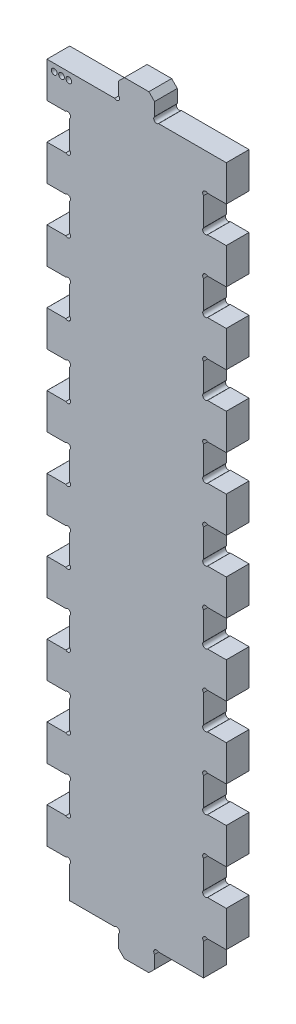
SolidWorks part; units mm, degrees
material "PVC Rigid"
ref_plane "Front Plane" through (0, 0, 0) normal (0, 0, 1) x (1, 0, 0)
ref_plane "Top Plane" through (0, 0, 0) normal (0, 1, 0) x (1, 0, 0)
ref_plane "Right Plane" through (0, 0, 0) normal (1, 0, 0) x (0, 0, -1)
sketch "Model" [suppressed]
  dimension "D3" = 0.7937
  dimension "D1" = 10
  dimension "D2" = 10
sketch "Sketch1" plane through (0, 0, 0) normal (0, 0, 1) x (1, 0, 0)
  line L1 (0, 0) -> (50, 0)
  line L2 (0, 0) -> (0, 200.0001)
  line L3 (0, 200.0001) -> (50, 200.0001)
  line L4 (50, 0) -> (50, 200.0001)
  dimension "D1" = 200.0001
  dimension "D2" = 50
extrude "Boss-Extrude1" add sketch "Sketch1" along normal blind 6.35
sketch "Sketch2" plane through (0, 0, 0) normal (0, 0, 1) x (1, 0, 0)
  line L0 (0, 100.0001) -> (50, 100.0001) construction
  line L1 (50, 200.0001) -> (0, 200.0001) construction
  line L2 (25, 200.0001) -> (25, 203.1751) construction
  line L3 (20, 206.3501) -> (30, 206.3501)
  line L4 (20, 206.3501) -> (20, 200.0001)
  line L5 (20, 200.0001) -> (30, 200.0001)
  line L6 (30, 206.3501) -> (30, 200.0001)
  line L7 (20, 206.3501) -> (30, 200.0001) construction
  line L8 (20, 200.0001) -> (30, 206.3501) construction
  line L9 (0, 200.0001) -> (0, 0) construction
  line L10 (50, 0) -> (50, 200.0001) construction
  line L11 (20, 0) -> (30, -6.35) construction
  line L12 (20, -6.35) -> (30, 0) construction
  line L13 (25, 0) -> (25, -3.175) construction
  line L14 (30, -6.35) -> (30, 0)
  line L15 (20, 0) -> (30, 0)
  line L16 (20, -6.35) -> (20, 0)
  line L17 (20, -6.35) -> (30, -6.35)
  dimension "D1" = 6.35
  dimension "D2" = 10
extrude "Boss-Extrude2" add sketch "Sketch2" along normal blind 6.35
sketch "Sketch3" plane through (0, 0, 6.35) normal (0, 0, 1) x (1, 0, 0)
  line L0 (25, 206.3501) -> (25, -6.35) construction
  line L1 (30, 206.3501) -> (20, 206.3501) construction
  line L2 (20, -6.35) -> (30, -6.35) construction
  line L3 (6.35, 200.0001) -> (6.35, 0) construction
  line L4 (20, 200.0001) -> (0, 200.0001) construction
  line L5 (0, 0) -> (20, 0) construction
  line L6 (0, 200.0001) -> (0, 0) construction
  line L7 (6.35, 0) -> (0, 0)
  line L8 (6.35, 0) -> (6.35, 10)
  line L9 (6.35, 10) -> (0, 10)
  line L10 (0, 0) -> (0, 10)
  line L11 (50, 0) -> (50, 10)
  line L12 (43.65, 10) -> (50, 10)
  line L13 (43.65, 0) -> (43.65, 10)
  line L14 (43.65, 0) -> (50, 0)
  dimension "D1" = 6.35
  dimension "D2" = 10
extrude "Cut-Extrude1" cut sketch "Sketch3" against normal blind 6.35
pattern_linear "LPattern2" count 10 spacing 20 along (0, 1, 0) of "Cut-Extrude1"
sketch "Sketch4" plane through (0, 0, 6.35) normal (0, 0, 1) x (1, 0, 0)
  line L0 (0, 10) -> (6.35, 0) construction
  line L1 (6.35, 10) -> (5.2275, 10) construction
  line L2 (0.5613, 0.5613) -> (5.7887, 0.5613) construction
  line L3 (0.5613, 0.5613) -> (0.5613, 9.4387) construction
  line L4 (0.5613, 9.4387) -> (5.7887, 9.4387) construction
  line L5 (5.7887, 0.5613) -> (5.7887, 9.4387) construction
  line L6 (0.5613, 0.5613) -> (5.7887, 9.4387) construction
  line L7 (0.5613, 9.4387) -> (5.7887, 0.5613) construction
  line L8 (6.35, 10) -> (0, 10) construction
  line L9 (6.35, 10) -> (6.35, 8.8775) construction
  line L10 (6.35, 0) -> (6.35, 10) construction
  line L11 (25, 206.3501) -> (25, -6.35) construction
  line L12 (30, 206.3501) -> (20, 206.3501) construction
  line L13 (20, -6.35) -> (30, -6.35) construction
  line L14 (44.2113, 9.4387) -> (44.2113, 20.5613) construction
  line L15 (43.65, 10) -> (43.65, 8.8775) construction
  line L16 (49.4387, 9.4387) -> (44.2113, 0.5613) construction
  line L17 (49.4387, 0.5613) -> (44.2113, 9.4387) construction
  line L18 (44.2113, 0.5613) -> (44.2113, 9.4387) construction
  line L19 (49.4387, 9.4387) -> (44.2113, 9.4387) construction
  line L20 (49.4387, 0.5613) -> (49.4387, 9.4387) construction
  line L21 (49.4387, 0.5613) -> (44.2113, 0.5613) construction
  line L22 (43.65, 10) -> (44.7725, 10) construction
  line L23 (5.7887, 9.4387) -> (5.7887, 20.5613) construction
  line L24 (50, 10) -> (43.65, 0) construction
  circle A0 centre (5.7887, 9.4387) radius 0.7938
  circle A4 centre (5.7887, 20.5613) radius 0.7938
  circle A7 centre (44.2113, 20.5613) radius 0.7937
  circle A8 centre (44.2113, 9.4387) radius 0.7937
  point P4 (3.175, 5)
  point P40 (46.825, 5)
  dimension "D1" = 1.5875
extrude "Cut-Extrude3" cut sketch "Sketch4" against normal blind 6.35
pattern_linear "LPattern3" count 9 spacing 20 along (0, 1, 0) of "Cut-Extrude3"
sketch "Sketch8" [suppressed] plane through (0, 0, 6.35) normal (0, 0, 1) x (1, 0, 0)
  line L0 (6.35, 200.0001) -> (6.35, 0) construction
  line L1 (20, 200.0001) -> (0, 200.0001) construction
  line L2 (0, 0) -> (20, 0) construction
  line L3 (0, 200.0001) -> (0, 0) construction
  line L4 (43.65, 200.0001) -> (43.65, 0) construction
  line L5 (0, 0) -> (6.35, 0)
  line L6 (0, 0) -> (0, 10)
  line L7 (0, 10) -> (6.35, 10)
  line L8 (6.35, 0) -> (6.35, 10)
  line L9 (50, 200.0001) -> (30, 200.0001) construction
  line L10 (30, 0) -> (50, 0) construction
  line L11 (50, 0) -> (50, 200.0001) construction
  line L12 (43.65, 10) -> (50, 10)
  line L13 (43.65, 10) -> (43.65, 20)
  line L14 (43.65, 20) -> (50, 20)
  line L15 (50, 10) -> (50, 20)
  dimension "D1" = 6.35
  dimension "D2" = 10
  dimension "D3" = 10
  dimension "D4" = 6.35
  dimension "D5" = 10
extrude "Cut-Extrude6" [suppressed] cut sketch "Sketch8" against normal through all
pattern_linear "LPattern4" [suppressed] count 10 spacing 20
sketch "Sketch9" [suppressed] plane through (0, 0, 6.35) normal (0, 0, 1) x (1, 0, 0)
  line L0 (0, 30) -> (6.35, 20) construction
  line L1 (6.35, 30) -> (5.2275, 30) construction
  line L2 (0.5613, 20.5613) -> (5.7887, 20.5613) construction
  line L3 (0.5613, 20.5613) -> (0.5613, 29.4388) construction
  line L4 (0.5613, 29.4388) -> (5.7887, 29.4388) construction
  line L5 (5.7887, 20.5613) -> (5.7887, 29.4388) construction
  line L6 (0.5613, 20.5613) -> (5.7887, 29.4388) construction
  line L7 (0.5613, 29.4388) -> (5.7887, 20.5613) construction
  line L8 (6.35, 30) -> (0, 30) construction
  line L9 (6.35, 30) -> (6.35, 28.8775) construction
  line L10 (6.35, 20) -> (6.35, 30) construction
  line L11 (43.65, 20) -> (50, 10) construction
  line L12 (43.65, 20) -> (44.7725, 20) construction
  line L13 (44.2113, 10.5613) -> (49.4387, 10.5613) construction
  line L14 (44.2113, 10.5613) -> (44.2113, 19.4387) construction
  line L15 (44.2113, 19.4387) -> (49.4387, 19.4387) construction
  line L16 (49.4387, 10.5613) -> (49.4387, 19.4387) construction
  line L17 (44.2113, 10.5613) -> (49.4387, 19.4387) construction
  line L18 (44.2113, 19.4387) -> (49.4387, 10.5613) construction
  line L19 (50, 20) -> (43.65, 20) construction
  line L20 (43.65, 20) -> (43.65, 18.8775) construction
  line L21 (43.65, 20) -> (43.65, 10) construction
  line L22 (50, 20) -> (50, 30) construction
  circle A0 centre (5.7887, 29.4388) radius 0.7938
  circle A1 centre (5.7887, 20.5613) radius 0.7938
  circle A2 centre (44.2113, 19.4387) radius 0.7937
  circle A3 centre (44.2113, 10.5613) radius 0.7937
  point P4 (3.175, 25)
  point P23 (46.825, 15)
  dimension "D1" = 1.5875
  dimension "D2" = 10
extrude "Cut-Extrude7" [suppressed] cut sketch "Sketch9" against normal through all
pattern_linear "LPattern5" [suppressed] count 9 spacing 20
sketch "Sketch10" [suppressed] plane through (0, 0, 6.35) normal (0, 0, 1) x (1, 0, 0)
  line L0 (0, 10) -> (6.35, 0) construction
  line L1 (5.2275, 10) -> (6.35, 10) construction
  line L2 (0.5613, 0.5613) -> (5.7887, 0.5613) construction
  line L3 (0.5613, 0.5613) -> (0.5613, 9.4387) construction
  line L4 (0.5613, 9.4387) -> (5.7887, 9.4387) construction
  line L5 (5.7887, 0.5613) -> (5.7887, 9.4387) construction
  line L6 (0.5613, 0.5613) -> (5.7887, 9.4387) construction
  line L7 (0.5613, 9.4387) -> (5.7887, 0.5613) construction
  line L8 (6.35, 10) -> (0, 10) construction
  line L9 (6.35, 10) -> (6.35, 8.8775) construction
  line L10 (6.35, 0) -> (6.35, 10) construction
  line L11 (6.35, 5) -> (3.175, 5) construction
  line L12 (0, 200.0001) -> (50, 0) construction
  line L13 (43.65, 200.0001) -> (50, 190.0001) construction
  line L14 (44.7725, 190.0001) -> (43.65, 190.0001) construction
  line L15 (44.2113, 190.5614) -> (49.4387, 190.5614) construction
  line L16 (44.2113, 190.5614) -> (44.2113, 199.4388) construction
  line L17 (44.2113, 199.4388) -> (49.4387, 199.4388) construction
  line L18 (49.4387, 190.5614) -> (49.4387, 199.4388) construction
  line L19 (44.2113, 190.5614) -> (49.4387, 199.4388) construction
  line L20 (44.2113, 199.4388) -> (49.4387, 190.5614) construction
  line L21 (43.65, 190.0001) -> (50, 190.0001) construction
  line L22 (43.65, 190.0001) -> (43.65, 191.1226) construction
  line L23 (43.65, 200.0001) -> (43.65, 190.0001) construction
  circle A0 centre (5.7887, 9.4387) radius 0.7938
  circle A2 centre (44.2113, 190.5614) radius 0.7937
  point P4 (3.175, 5)
  point P28 (46.825, 195.0001)
  dimension "D1" = 1.5875
  dimension "D2" = 1.5875
extrude "Cut-Extrude8" [suppressed] cut sketch "Sketch10" against normal through all
chamfer "Chamfer1" distance 1.5875 angle 45 4 edges at (30, -6.35, 3.175) (20, -6.35, 3.175) (20, 206.3501, 3.175) (30, 206.3501, 3.175)
sketch "Sketch5" plane through (0, 0, 6.35) normal (0, 0, 1) x (1, 0, 0)
  line L0 (6.35, 180.0001) -> (0, 190.0001) construction
  line L1 (6.35, 190.0001) -> (5.2275, 190.0001) construction
  line L2 (0.5613, 180.5614) -> (5.7887, 180.5614) construction
  line L3 (0.5613, 180.5614) -> (0.5613, 189.4388) construction
  line L4 (0.5613, 189.4388) -> (5.7887, 189.4388) construction
  line L5 (5.7887, 180.5614) -> (5.7887, 189.4388) construction
  line L6 (0.5613, 180.5614) -> (5.7887, 189.4388) construction
  line L7 (0.5613, 189.4388) -> (5.7887, 180.5614) construction
  line L8 (6.35, 190.0001) -> (0, 190.0001) construction
  line L9 (6.35, 190.0001) -> (6.35, 188.8776) construction
  line L10 (6.35, 181.1226) -> (6.35, 190.0001) construction
  line L15 (25, 206.3501) -> (25, -6.35) construction
  line L16 (28.4125, 206.3501) -> (21.5875, 206.3501) construction
  line L17 (21.5875, -6.35) -> (28.4125, -6.35) construction
  line L20 (43.65, 190.0001) -> (43.65, 188.8776) construction
  line L21 (49.4387, 189.4388) -> (44.2113, 180.5614) construction
  line L22 (49.4387, 180.5614) -> (44.2113, 189.4388) construction
  line L23 (44.2113, 180.5614) -> (44.2113, 189.4388) construction
  line L24 (49.4387, 189.4388) -> (44.2113, 189.4388) construction
  line L25 (49.4387, 180.5614) -> (49.4387, 189.4388) construction
  line L26 (49.4387, 180.5614) -> (44.2113, 180.5614) construction
  line L27 (43.65, 190.0001) -> (44.7725, 190.0001) construction
  line L28 (43.65, 180.0001) -> (50, 190.0001) construction
  line L29 (50, 100.0001) -> (0, 100.0001) construction
  arc A0 (5.2275, 180.0001) -> (6.35, 181.1226) centre (5.7887, 180.5614) ccw construction
  circle A1 centre (5.7887, 189.4388) radius 0.7938
  circle A4 centre (44.2113, 189.4388) radius 0.7937
  point P6 (3.175, 185.0001)
  point P51 (46.825, 185.0001)
  point P56 (25, 100.0001)
  dimension "D1" = 1.5875
extrude "Cut-Extrude4" cut sketch "Sketch5" against normal blind 6.35
sketch "Sketch11" plane through (0, 0, 0) normal (0, 0, 1) x (1, 0, 0)
  line L0 (28.4125, 206.3501) -> (21.5875, 206.3501) construction
  line L11 (20, 201.1226) -> (20, 200.0001) construction
  line L13 (20, 200.0001) -> (18.8775, 200.0001) construction
  line L15 (25, 206.3501) -> (25, -6.35) construction
  line L18 (30, 200.0001) -> (31.1225, 200.0001) construction
  line L19 (30, 201.1226) -> (30, 200.0001) construction
  line L29 (50, 100.0001) -> (0, 100.0001) construction
  circle A2 centre (19.4387, 200.5614) radius 0.7937
  circle A3 centre (30.5613, 200.5614) radius 0.7937
  circle A5 centre (19.4387, -0.5613) radius 0.7937
  circle A6 centre (30.5613, -0.5613) radius 0.7937
  point P56 (25, 100.0001)
  dimension "D1" = 1.5875
  dimension "D2" = 19.4387
  dimension "D3" = 100.0001
  dimension "D4" = 200.0001
extrude "Cut-Extrude10" cut sketch "Sketch11" along normal through all
sketch "Sketch6" plane through (0, 0, 6.35) normal (0, 0, 1) x (1, 0, 0)
  line L0 (6.604, 2.032) -> (43.65, 2.032) construction
  line L1 (43.65, 8.8775) -> (43.65, 0) construction
  line L2 (6.35, 0) -> (18.8775, 0) construction
  line L4 (0, 20) -> (0, 10) construction
  text T0 "COR" font "Consolas" height 3.5
  dimension "D1" = 2.032
  dimension "D2" = 6.604
extrude "Cut-Extrude5" [suppressed] cut sketch "Sketch6" against normal blind 2.54
sketch "Sketch12" [suppressed]
  dimension "D1" = 2.032
  dimension "D2" = 6.604
extrude "Cut-Extrude11" [suppressed] cut sketch "Sketch12" against normal blind 2.54
sketch "Sketch13" plane through (0, 0, 6.35) normal (0, 0, 1) x (1, 0, 0)
  line L0 (0, 10) -> (6.35, 0) construction
  line L1 (5.2275, 10) -> (0, 10) construction
  line L2 (6.337, -0.0127) -> (0.013, -0.0127)
  line L3 (6.337, -0.0127) -> (6.337, 10.0127)
  line L4 (6.337, 10.0127) -> (0.013, 10.0127)
  line L5 (0.013, -0.0127) -> (0.013, 10.0127)
  line L6 (6.337, -0.0127) -> (0.013, 10.0127) construction
  line L7 (6.337, 10.0127) -> (0.013, -0.0127) construction
  line L8 (25, 206.3501) -> (25, -6.35) construction
  line L9 (28.4125, 206.3501) -> (21.5875, 206.3501) construction
  line L10 (21.5875, -6.35) -> (28.4125, -6.35) construction
  line L11 (43.663, 10.0127) -> (49.987, -0.0127) construction
  line L12 (43.663, -0.0127) -> (49.987, 10.0127) construction
  line L13 (50, 10) -> (43.65, 0) construction
  line L14 (49.987, -0.0127) -> (49.987, 10.0127)
  line L15 (43.663, 10.0127) -> (49.987, 10.0127)
  line L16 (43.663, -0.0127) -> (43.663, 10.0127)
  line L17 (43.663, -0.0127) -> (49.987, -0.0127)
  arc A0 (6.35, 8.8775) -> (5.2275, 10) centre (5.7887, 9.4387) ccw construction
  point P4 (3.175, 5)
  point P26 (46.825, 5)
  dimension "D1" = 0.0127
extrude "Cut-Extrude12" cut sketch "Sketch13" against normal through all
pattern_linear "LPattern6" count 10 spacing 20 along (0, 1, 0) of "Cut-Extrude12"
sketch "Sketch14" [suppressed] plane through (0, 0, 6.35) normal (0, 0, 1) x (1, 0, 0)
  line L0 (0, 10) -> (6.35, 0) construction
  line L1 (5.2275, 10) -> (0, 10) construction
  line L2 (0.013, -0.0127) -> (6.337, -0.0127)
  line L3 (0.013, -0.0127) -> (0.013, 10.0127)
  line L4 (0.013, 10.0127) -> (6.337, 10.0127)
  line L5 (6.337, -0.0127) -> (6.337, 10.0127)
  line L6 (0.013, -0.0127) -> (6.337, 10.0127) construction
  line L7 (0.013, 10.0127) -> (6.337, -0.0127) construction
  line L8 (43.65, 20) -> (50, 10) construction
  line L9 (50, 20) -> (44.7725, 20) construction
  line L10 (43.663, 9.9873) -> (49.987, 9.9873)
  line L11 (43.663, 9.9873) -> (43.663, 20.0127)
  line L12 (43.663, 20.0127) -> (49.987, 20.0127)
  line L13 (49.987, 9.9873) -> (49.987, 20.0127)
  line L14 (43.663, 9.9873) -> (49.987, 20.0127) construction
  line L15 (43.663, 20.0127) -> (49.987, 9.9873) construction
  arc A0 (6.35, 8.8775) -> (5.2275, 10) centre (5.7887, 9.4387) ccw construction
  arc A1 (44.7725, 20) -> (43.65, 18.8775) centre (44.2113, 19.4387) ccw construction
  point P4 (3.175, 5)
  point P9 (46.825, 15)
  dimension "D1" = 0.0127
  dimension "D2" = 0.0127
extrude "Cut-Extrude13" [suppressed] cut sketch "Sketch14" against normal through all
pattern_linear "LPattern7" [suppressed] count 10 spacing 20
sketch "Sketch15" plane through (0, 0, 6.35) normal (0, 0, 1) x (1, 0, 0)
  line L1 (0, 200.0001) -> (2.032, 200.0001) construction
  line L2 (0, 200.0001) -> (0, 197.9681) construction
  line L3 (0, 197.9681) -> (2.032, 197.9681) construction
  line L4 (2.032, 200.0001) -> (2.032, 197.9681) construction
  circle A0 centre (2.032, 197.9681) radius 0.7938
  dimension "D2" = 1.5875
  dimension "D1" = 2.032
extrude "Cut-Extrude14" cut sketch "Sketch15" against normal blind 3.175
pattern_linear "LPattern8" count 3 spacing 2.032 along (1, 0, 0) of "Cut-Extrude14"
equation "\"tHeight\"=0.25"
equation "\"D1@Sketch2\"=\"tHeight\""
equation "\"tWidth\"=0.393701"
equation "\"D2@Sketch2\"=\"tWidth\""
equation "\"D1@Sketch1\"=\"tWidth\"*20"
equation "\"D1@Sketch3\"=\"tHeight\""
equation "\"D2@Sketch3\"=\"tWidth\""
equation "\"D3@LPattern2\"=\"tWidth\"*2"
equation "\"D3@LPattern3\"=\"tWidth\"*2"
equation "\"D1@Sketch8\"=\"tHeight\""
equation "\"D2@Sketch8\"=\"tWidth\""
equation "\"D3@Sketch8\"=\"tWidth\""
equation "\"D4@Sketch8\"=\"tHeight\""
equation "\"D5@Sketch8\"=\"tWidth\""
equation "\"D3@LPattern4\"=\"tWidth\"*2"
equation "\"D3@LPattern5\"=\"tWidth\"*2"
equation "\"D2@Sketch9\"=\"tWidth\""
equation "\"tol\"=0.0005"
equation "\"D1@Sketch13\"=\"tol\""
equation "\"D3@LPattern6\"=\"tWidth\"*2"
equation "\"D1@Sketch14\"=\"tol\""
equation "\"D2@Sketch14\"=\"tol\""
equation "\"version\"= 3"
equation "\"D1@LPattern8\"=\"version\""
